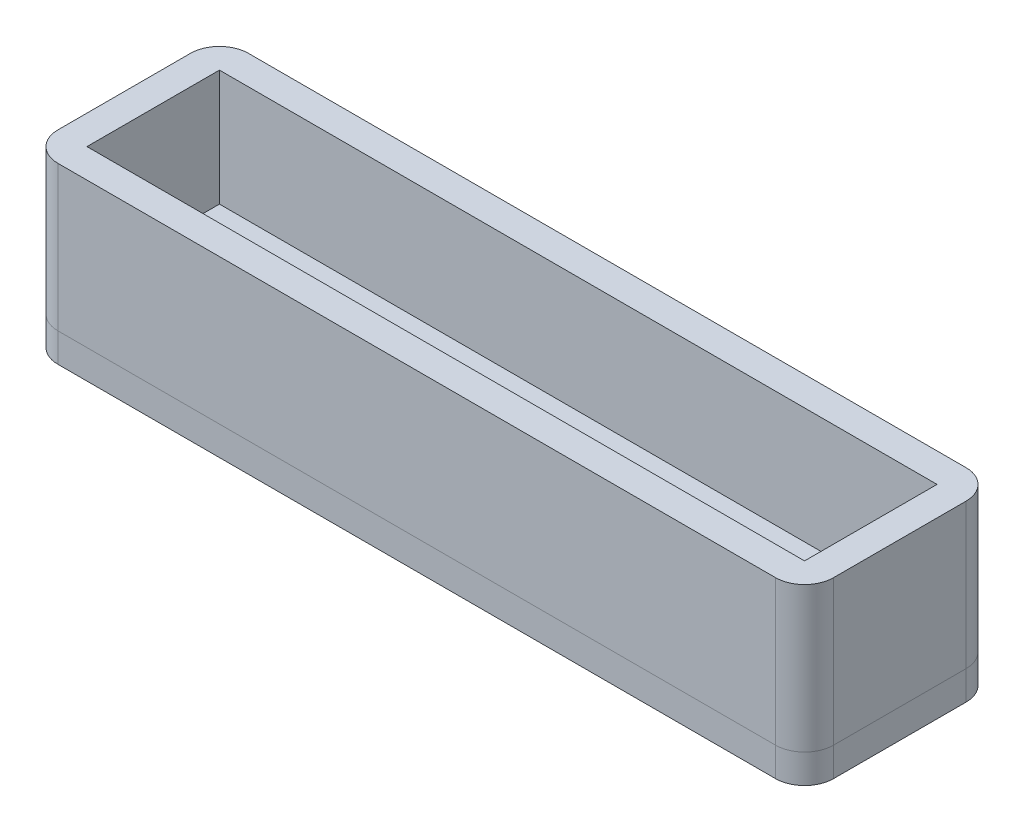
SolidWorks part; units mm, degrees
other "Felt Pad"
other "Main Body"
ref_plane "Front Plane" through (0, 0, 0) normal (0, 0, 1) x (1, 0, 0)
ref_plane "Top Plane" through (0, 0, 0) normal (0, 1, 0) x (1, 0, 0)
ref_plane "Right Plane" through (0, 0, 0) normal (1, 0, 0) x (0, 0, -1)
sketch "Sketch1" plane through (0, 0, 0) normal (0, 1, 0) x (1, 0, 0)
  line L1 (0, 0) -> (74.2, 0)
  line L2 (0, 0) -> (0, 13.7)
  line L3 (0, 13.7) -> (74.2, 13.7)
  line L4 (74.2, 0) -> (74.2, 13.7)
  line L5 (0, 0) -> (74.2, 13.7) construction
  line L6 (0, 13.7) -> (74.2, 0) construction
  point P4 (37.1, 6.85)
  dimension "D1" = 74.2
  dimension "D2" = 13.7
extrude "Boss-Extrude1" add sketch "Sketch1" along normal blind 3
sketch "Sketch2" plane through (0, 0, 0) normal (0, -1, 0) x (1, 0, 0)
  line L0 (77.2, 3) -> (-3, 3)
  line L1 (-3, 3) -> (-3, -16.7)
  line L2 (-3, -16.7) -> (77.2, -16.7)
  line L3 (77.2, -16.7) -> (77.2, 3)
  line L4 (0, 0) -> (0, -13.7)
  line L5 (0, -13.7) -> (74.2, -13.7)
  line L6 (74.2, -13.7) -> (74.2, 0)
  line L7 (74.2, 0) -> (0, 0)
  line L8 (0, 0) -> (0, -13.7)
  line L9 (0, -13.7) -> (74.2, -13.7)
  line L10 (74.2, -13.7) -> (74.2, 0)
  line L11 (74.2, 0) -> (0, 0)
  dimension "D1" = 0
  dimension "D2" = 3
extrude "Boss-Extrude2" add sketch "Sketch2" against normal blind 15
fillet "Fillet1" radius 3 4 edges at (77.2, 7.5, 3) (77.2, 7.5, -16.7) (-3, 7.5, -16.7) (-3, 7.5, 3)
sketch "Sketch3" plane through (0, 0, 0) normal (0, -1, 0) x (1, 0, 0)
  line L4 (77.2, -13.7) -> (77.2, 0)
  line L5 (74.2, 3) -> (0, 3)
  line L6 (-3, 0) -> (-3, -13.7)
  line L7 (0, -16.7) -> (74.2, -16.7)
  line L8 (77.2, -13.7) -> (77.2, 0)
  line L9 (74.2, 3) -> (0, 3)
  line L10 (-3, 0) -> (-3, -13.7)
  line L11 (0, -16.7) -> (74.2, -16.7)
  arc A4 (77.2, 0) -> (74.2, 3) centre (74.2, 0) ccw
  arc A5 (0, 3) -> (-3, 0) centre (0, 0) ccw
  arc A6 (-3, -13.7) -> (0, -16.7) centre (0, -13.7) ccw
  arc A7 (74.2, -16.7) -> (77.2, -13.7) centre (74.2, -13.7) ccw
  arc A8 (77.2, 0) -> (74.2, 3) centre (74.2, 0) ccw
  arc A9 (0, 3) -> (-3, 0) centre (0, 0) ccw
  arc A10 (-3, -13.7) -> (0, -16.7) centre (0, -13.7) ccw
  arc A11 (74.2, -16.7) -> (77.2, -13.7) centre (74.2, -13.7) ccw
  dimension "D1" = 0
extrude "Boss-Extrude3" add sketch "Sketch3" along normal blind 3 separate body
